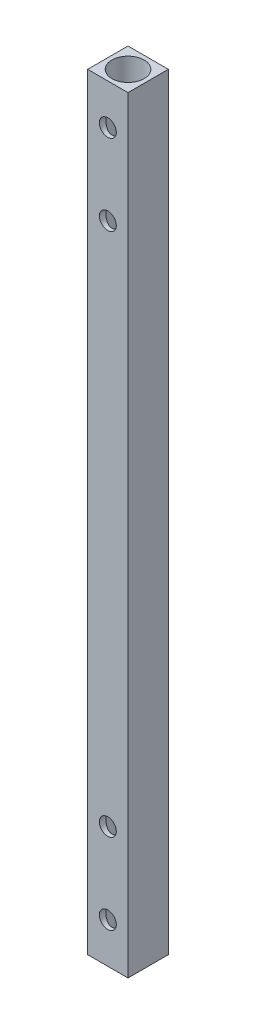
SolidWorks part; units mm, degrees
ref_plane "前视基准面" through (0, 0, 0) normal (0, 0, 1) x (1, 0, 0)
ref_plane "上视基准面" through (0, 0, 0) normal (0, 1, 0) x (1, 0, 0)
ref_plane "右视基准面" through (0, 0, 0) normal (1, 0, 0) x (0, 0, -1)
sketch "草图1" plane through (0, 0, 0) normal (0, 1, 0) x (1, 0, 0)
  line L1 (-5, -5) -> (5, -5)
  line L2 (-5, -5) -> (-5, 5)
  line L3 (-5, 5) -> (5, 5)
  line L4 (5, -5) -> (5, 5)
  line L5 (-5, -5) -> (5, 5) construction
  line L6 (-5, 5) -> (5, -5) construction
  point P0 (0, 0)
  dimension "D1" = 10
  dimension "D2" = 10
extrude "凸台-拉伸1" add sketch "草图1" along normal blind 190
sketch "草图2" plane through (0, 0, 5) normal (0, 0, 1) x (1, 0, 0)
  line L0 (-5, 95) -> (49995, 95) construction
  line L1 (-5, 190) -> (-5, 0) construction
  line L2 (-5, 0) -> (5, 0) construction
  circle A1 centre (0, 10) radius 2.1
  circle A2 centre (0, 30) radius 2.1
  circle A3 centre (0, 180) radius 2.1
  circle A4 centre (0, 160) radius 2.1
  point P6 (-5, 95)
  dimension "D1" = 4.2
  dimension "D2" = 10
  dimension "D3" = 20
extrude "切除-拉伸1" cut sketch "草图2" against normal blind 200
sketch "草图3" plane through (0, 0, 0) normal (0, -1, 0) x (1, 0, 0)
  circle A0 centre (0, 0) radius 4
  dimension "D1" = 8
extrude "切除-拉伸2" cut sketch "草图3" against normal through all
